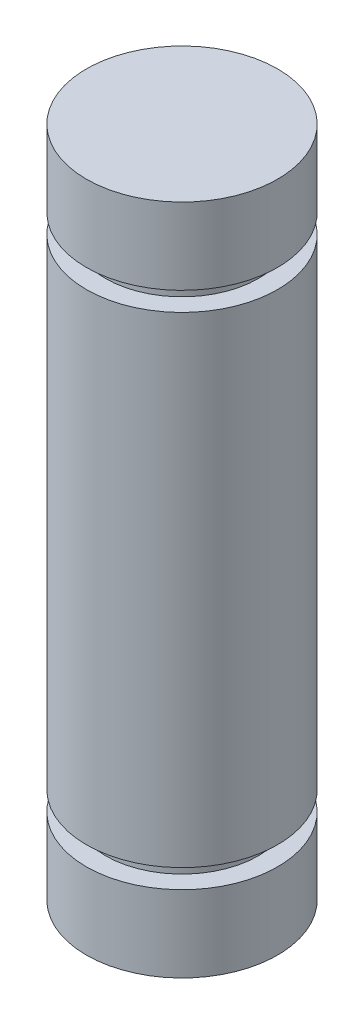
SolidWorks part; units mm, degrees
ref_plane "Front Plane" through (0, 0, 0) normal (0, 0, 1) x (1, 0, 0)
ref_plane "Top Plane" through (0, 0, 0) normal (0, 1, 0) x (1, 0, 0)
ref_plane "Right Plane" through (0, 0, 0) normal (1, 0, 0) x (0, 0, -1)
sketch "Sketch1" plane through (0, 0, 0) normal (0, 1, 0) x (1, 0, 0)
  circle A0 centre (0, 0) radius 6.35
  dimension "D1" = 12.7
extrude "Boss-Extrude2" add sketch "Sketch1" along normal blind 31.9405
sketch "Sketch4" plane through (0, 31.9405, 0) normal (0, 1, 0) x (1, 0, 0)
  circle A0 centre (0, 0) radius 5.08
  dimension "D1" = 10.16
extrude "Boss-Extrude3" add sketch "Sketch4" along normal blind 1.27
sketch "Sketch5" plane through (0, 33.2105, 0) normal (0, 1, 0) x (1, 0, 0)
  circle A0 centre (0, 0) radius 6.35
  dimension "D1" = 12.7
extrude "Boss-Extrude4" add sketch "Sketch5" along normal blind 5.08
sketch "Sketch6" plane through (0, 0, 0) normal (0, -1, 0) x (1, 0, 0)
  circle A0 centre (0, 0) radius 5.08
  dimension "D1" = 10.16
extrude "Boss-Extrude5" add sketch "Sketch6" along normal blind 1.27
sketch "Sketch7" plane through (0, -1.27, 0) normal (0, -1, 0) x (1, 0, 0)
  circle A0 centre (0, 0) radius 6.35
  dimension "D1" = 12.7
extrude "Boss-Extrude6" add sketch "Sketch7" along normal blind 5.08
